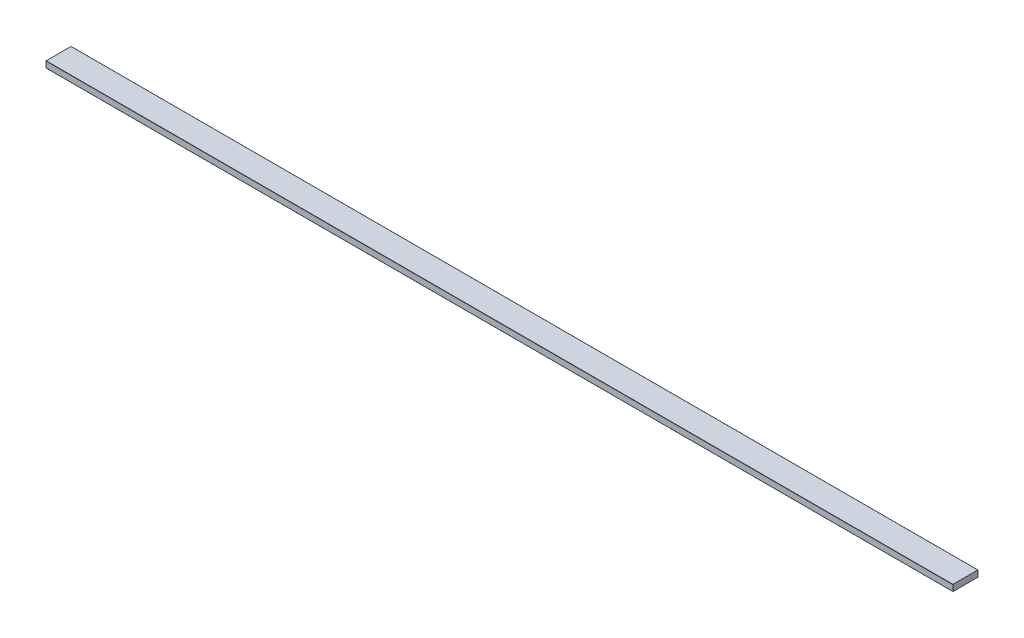
SolidWorks part; units mm, degrees
ref_plane "Front Plane" through (0, 0, 0) normal (0, 0, 1) x (1, 0, 0)
ref_plane "Top Plane" through (0, 0, 0) normal (0, 1, 0) x (1, 0, 0)
ref_plane "Right Plane" through (0, 0, 0) normal (1, 0, 0) x (0, 0, -1)
sketch "Sketch1" plane through (0, 0, 0) normal (0, 1, 0) x (1, 0, 0)
  line L1 (457.2, -12.7) -> (-457.2, -12.7)
  line L2 (457.2, -12.7) -> (457.2, 12.7)
  line L3 (457.2, 12.7) -> (-457.2, 12.7)
  line L4 (-457.2, -12.7) -> (-457.2, 12.7)
  line L5 (457.2, -12.7) -> (-457.2, 12.7) construction
  line L6 (457.2, 12.7) -> (-457.2, -12.7) construction
  point P0 (0, 0)
  dimension "Length" = 914.4
  dimension "Width" = 25.4
sketch "Sketch2" plane through (0, 0, 0) normal (1, 0, 0) x (0, 0, -1)
  line L0 (12.7, 3.175) -> (12.7, -3.175) construction
  point P2 (12.7, 0)
  dimension "Thickness" = 6.35
sketch "Sketch3" plane through (0, 0, 0) normal (0, 1, 0) x (1, 0, 0)
  line L1 (-457.2, 12.7) -> (457.2, 12.7)
  line L2 (-457.2, 12.7) -> (-457.2, -12.7)
  line L3 (-457.2, -12.7) -> (457.2, -12.7)
  line L4 (457.2, 12.7) -> (457.2, -12.7)
extrude "Boss-Extrude1" add sketch "Sketch3" against normal up to vertex (3.175 mm away) and the other way up to vertex (3.175 mm away) up to point (0, -3.175, -12.7) other way up to point (0, 3.175, -12.7)
fillet "Fillet1" radius 0.2095 4 edges at (0, -3.175, 12.7) (0, -3.175, -12.7) (0, 3.175, -12.7) (0, 3.175, 12.7)
equation "\"D1@Fillet1\" = \"Thickness@Sketch2\" * .033"
